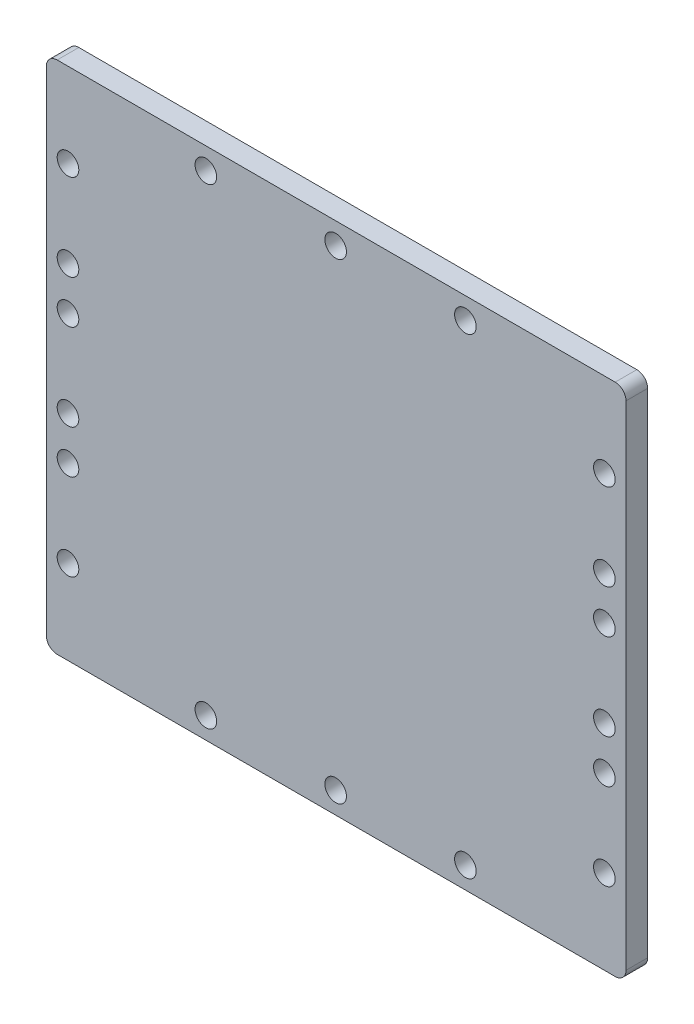
SolidWorks part; units mm, degrees
material "自訂玻璃纖維"
ref_plane "前基準面" through (0, 0, 0) normal (0, 0, 1) x (1, 0, 0)
ref_plane "上基準面" through (0, 0, 0) normal (0, 1, 0) x (1, 0, 0)
ref_plane "右基準面" through (0, 0, 0) normal (1, 0, 0) x (0, 0, -1)
sketch "草圖1" plane through (0, 0, 0) normal (0, 0, 1) x (1, 0, 0)
  line L1 (-35.2005, 20.825) -> (16.3995, 20.825)
  line L2 (-36.2005, 19.825) -> (-36.2005, -25.775)
  line L3 (-35.2005, -26.775) -> (16.3995, -26.775)
  line L4 (17.3995, 19.825) -> (17.3995, -25.775)
  circle A0 centre (-9.4505, 18.825) radius 1
  circle A1 centre (-9.4505, -24.775) radius 1
  arc A2 (-36.2005, -25.775) -> (-35.2005, -26.775) centre (-35.2005, -25.775) ccw
  arc A3 (16.3995, -26.775) -> (17.3995, -25.775) centre (16.3995, -25.775) ccw
  arc A4 (16.3995, 20.825) -> (17.3995, 19.825) centre (16.3995, 19.825) cw
  arc A5 (-35.2005, 20.825) -> (-36.2005, 19.825) centre (-35.2005, 19.825) ccw
  circle A6 centre (15.3995, 1.025) radius 1
  circle A7 centre (-34.2005, 1.025) radius 1
  circle A8 centre (-34.2005, -6.975) radius 1
  circle A9 centre (15.3995, -6.975) radius 1
  circle A10 centre (-34.2005, 13.025) radius 1
  circle A11 centre (-34.2005, 5.025) radius 1
  circle A12 centre (-34.2005, -10.975) radius 1
  circle A13 centre (-34.2005, -18.975) radius 1
  circle A14 centre (15.3995, 13.025) radius 1
  circle A15 centre (15.3995, 5.025) radius 1
  circle A16 centre (15.3995, -10.975) radius 1
  circle A17 centre (15.3995, -18.975) radius 1
  circle A18 centre (-21.4505, 18.825) radius 1
  circle A19 centre (2.5495, 18.825) radius 1
  circle A21 centre (-21.4505, -24.775) radius 1
  circle A22 centre (2.5495, -24.775) radius 1
  point P10 (-36.2005, -26.775)
  point P15 (17.3995, 20.825)
  point P18 (-36.2005, 20.825)
  point P27 (-36.2005, -2.975)
  point P30 (17.3995, -2.975)
  dimension "D3" = 2
  dimension "D4" = 2
  dimension "D5" = 2
  dimension "D6" = 1
  dimension "D8" = 2
  dimension "D9" = 2
  dimension "D10" = 2
  dimension "D11" = 2
  dimension "D12" = 8
  dimension "D13" = 4
  dimension "D14" = 8
  dimension "D15" = 4
  dimension "D16" = 2
  dimension "D7" = 26.75
  dimension "D17" = 2
  dimension "D19" = 4
  dimension "D20" = 2
  dimension "D21" = 2
  dimension "D23" = 4
  dimension "D24" = 2
  dimension "D25" = 8
  dimension "D26" = 4
  dimension "D27" = 2
  dimension "D28" = 8
  dimension "D29" = 4
  dimension "D30" = 2
  dimension "D31" = 2
  dimension "D32" = 2
  dimension "D33" = 12
  dimension "D34" = 12
  dimension "D35" = 24
  dimension "D36" = 12
  dimension "D37" = 2
  dimension "D1" = 47.6
  dimension "D2" = 53.6
  dimension "D18" = 8
  dimension "D22" = 8
extrude "填料-伸長1" add sketch "草圖1" along normal blind 2
